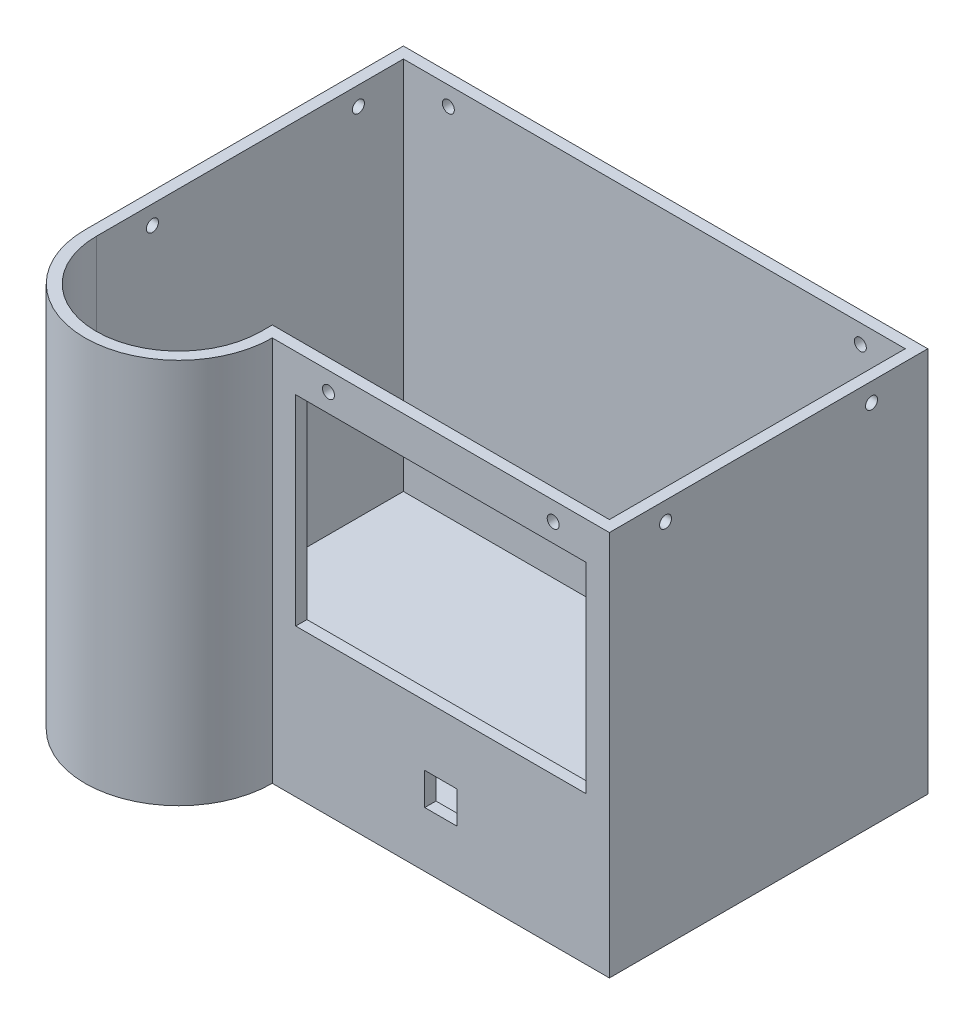
SolidWorks part; units mm, degrees
ref_plane "Ön Düzlem" through (0, 0, 0) normal (0, 0, 1) x (1, 0, 0)
ref_plane "Üst Düzlem" through (0, 0, 0) normal (0, 1, 0) x (1, 0, 0)
ref_plane "Sağ Düzlem" through (0, 0, 0) normal (1, 0, 0) x (0, 0, -1)
sketch "Çizim1" plane through (0, 0, 0) normal (0, 1, 0) x (1, 0, 0)
  line L1 (50, 0) -> (140, 0)
  line L2 (0, 0) -> (0, 85)
  line L3 (0, 85) -> (140, 85)
  line L4 (140, 0) -> (140, 85)
  arc A0 (0, 0) -> (50, 0) centre (25, 0) ccw
  circle A1 centre (25, 0) radius 13.8
  dimension "D3" = 50
  dimension "D4" = 27.6
  dimension "D1" = 140
  dimension "D2" = 85
extrude "Yükseklik-Ekstrüzyon1" add sketch "Çizim1" along normal blind 3
sketch "Çizim2" plane through (0, 3, 0) normal (0, 1, 0) x (1, 0, 0)
  line L0 (0, 85) -> (140, 85)
  line L1 (140, 85) -> (140, 0)
  line L2 (140, 0) -> (50, 0)
  line L3 (0, 0) -> (0, 85)
  line L4 (3, 3) -> (3, 0)
  line L5 (3, 82) -> (137, 82)
  line L6 (3, 82) -> (3, 3)
  line L7 (47, 3) -> (137, 3)
  line L8 (137, 82) -> (137, 3)
  line L9 (46.9803, 0.9303) -> (47, 0)
  line L10 (47, 0) -> (47, 3)
  arc A0 (50, 0) -> (0, 0) centre (25, 0) cw
  arc A3 (3, 0) -> (46.9803, 0.9303) centre (25, 0) ccw
  arc M17 (0, 0) -> (50, 0) centre (25, 0) ccw
  line M18 (50, 0) -> (140, 0)
  line M19 (140, 0) -> (140, 85)
  line M20 (140, 85) -> (0, 85)
  line M21 (0, 85) -> (0, 0)
  dimension "D1" = 3
  dimension "D2" = 3
  dimension "D3" = 134
  dimension "D4" = 79
extrude "Yükseklik-Ekstrüzyon2" add sketch "Çizim2" along normal blind 100 contours A3 L4 L6 L5 L8 L7 L10 M21 M17 M18 M19 M20
sketch "Çizim3" plane through (0, 0, 0) normal (0, 0, 1) x (1, 0, 0)
  line L0 (50, 103) -> (140, 103) construction
  line L1 (56.25, 93) -> (133.75, 93)
  line L2 (56.25, 93) -> (56.25, 39.5)
  line L3 (56.25, 39.5) -> (133.75, 39.5)
  line L4 (133.75, 93) -> (133.75, 39.5)
  line L5 (95, 103) -> (95, 0) construction
  line L6 (50, 0) -> (140, 0) construction
  dimension "D1" = 77.5
  dimension "D2" = 53.5
  dimension "D3" = 38.75
  dimension "D4" = 10
extrude "Kes-Ekstrüzyon1" cut sketch "Çizim3" against normal blind 10
sketch "Çizim4" plane through (0, 0, 0) normal (0, 0, 1) x (1, 0, 0)
  line L0 (95, 103) -> (95, 0) construction
  line L1 (82.5, 28.862) -> (107.5, 28.862) construction
  line L2 (82.5, 28.862) -> (82.5, 5) construction
  line L3 (82.5, 5) -> (107.5, 5) construction
  line L4 (107.5, 28.862) -> (107.5, 5) construction
  line L5 (50, 103) -> (140, 103) construction
  line L6 (50, 0) -> (140, 0) construction
  line L8 (90.7, 23.362) -> (99.3, 23.362)
  line L9 (90.7, 23.362) -> (90.7, 14.762)
  line L10 (90.7, 14.762) -> (99.3, 14.762)
  line L11 (99.3, 23.362) -> (99.3, 14.762)
  dimension "D1" = 25
  dimension "D2" = 23.862
  dimension "D3" = 12.5
  dimension "D4" = 5
  dimension "D5" = 8.6
  dimension "D6" = 8.6
  dimension "D7" = 4.3
  dimension "D8" = 5.5
extrude "Kes-Ekstrüzyon2" cut sketch "Çizim4" against normal blind 10
sketch "Çizim5" plane through (0, 0, 0) normal (0, 0, 1) x (1, 0, 0)
  line L0 (50, 103) -> (140, 103) construction
  line L2 (50, 103) -> (50, 0) construction
  circle A0 centre (65, 98) radius 1.6
  circle A1 centre (125, 98) radius 1.6
  dimension "D1" = 5
  dimension "D2" = 15
  dimension "D3" = 2
extrude "Kes-Ekstrüzyon3" cut sketch "Çizim5" against normal blind 10
sketch "Çizim6" plane through (140, 0, 0) normal (1, 0, 0) x (0, 0, -1)
  line L0 (0, 103) -> (85, 103) construction
  line L1 (0, 103) -> (0, 0) construction
  circle A0 centre (15, 98) radius 1.6
  circle A1 centre (70, 98) radius 1.6
  dimension "D1" = 5
  dimension "D2" = 15
  dimension "D3" = 2
extrude "Kes-Ekstrüzyon4" cut sketch "Çizim6" against normal blind 10
sketch "Çizim7" plane through (0, 0, -85) normal (0, 0, -1) x (-1, 0, 0)
  line L0 (-140, 103) -> (0, 103) construction
  line L1 (-140, 103) -> (-140, 0) construction
  circle A0 centre (-125, 98) radius 1.6
  circle A1 centre (-15, 98) radius 1.6
  dimension "D1" = 5
  dimension "D2" = 15
  dimension "D3" = 2
extrude "Kes-Ekstrüzyon5" cut sketch "Çizim7" against normal blind 10
sketch "Çizim8" plane through (0, 0, 0) normal (-1, 0, 0) x (0, 0, 1)
  line L0 (-85, 103) -> (0, 103) construction
  line L1 (-85, 103) -> (-85, 0) construction
  circle A0 centre (-70, 98) radius 1.6
  circle A1 centre (-15, 98) radius 1.6
  dimension "D1" = 5
  dimension "D2" = 15
  dimension "D3" = 2
extrude "Kes-Ekstrüzyon6" cut sketch "Çizim8" against normal blind 10
